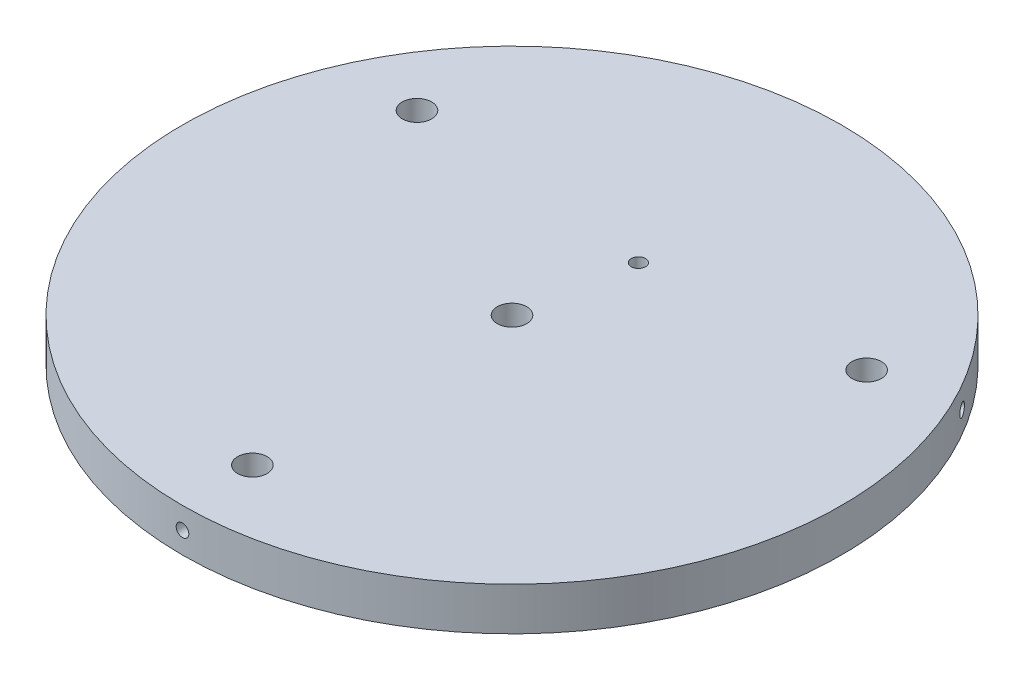
SolidWorks part; units mm, degrees
ref_plane "Front Plane" through (0, 0, 0) normal (0, 0, 1) x (1, 0, 0)
ref_plane "Top Plane" through (0, 0, 0) normal (0, 1, 0) x (1, 0, 0)
ref_plane "Right Plane" through (0, 0, 0) normal (1, 0, 0) x (0, 0, -1)
sketch "Sketch1" plane through (0, 0, 0) normal (0, 1, 0) x (1, 0, 0)
  line L0 (0, 0) -> (-63.2415, 36.5125) construction
  line L1 (0, 0) -> (0, -73.025) construction
  line L2 (0, 0) -> (63.2415, 36.5125) construction
  line L3 (0, 0) -> (7.2777, 23.8043) construction
  circle A0 centre (0, 0) radius 73.025
  circle A1 centre (-49.8233, 28.7655) radius 3.2639
  circle A2 centre (49.8233, 28.7655) radius 3.2639
  circle A3 centre (0, -57.531) radius 3.2639
  circle A4 centre (0, 0) radius 3.2639
  circle A5 centre (7.2777, 23.8043) radius 1.5875 construction
  point P15 (0, 0)
  dimension "D1" = 146.05
  dimension "D4" = 6.5278
  dimension "D7" = 6.5278
  dimension "D8" = 3.175
  dimension "D2" = 120
  dimension "D3" = 120
  dimension "D5" = 57.531
  dimension "D9" = 24.892
  dimension "D10" = 163
  dimension "D6" = 3
extrude "Boss-Extrude1" add sketch "Sketch1" along normal blind 9.525
ref_plane "Plane1" through (0, 0, 73.025) normal (0, 0, 1) x (1, 0, 0)
sketch "Sketch3" plane through (0, 0, 0) normal (0, 0, 1) x (1, 0, 0)
  line L0 (0, 0) -> (0, 9.525) construction
  line L1 (73.025, 9.525) -> (-73.025, 9.525) construction
sketch "Sketch4" plane through (0, 0, 73.025) normal (0, 0, 1) x (1, 0, 0)
  line L0 (0, 0) -> (0, 9.525) construction
  circle A0 centre (0, 4.7625) radius 1.397
  dimension "D1" = 2.794
extrude "Cut-Extrude1" cut sketch "Sketch4" against normal blind 6.35
pattern_circular "CirPattern1" count 3 over 360 about axis through (0, 0, 0) along (0, 1, 0) of "Cut-Extrude1"
sketch "Sketch5" plane through (0, 9.525, 0) normal (0, 1, 0) x (1, 0, 0)
  circle A0 centre (3.9182, 24.0893) radius 1.5875
  point P0 (3.9182, 24.0893)
  dimension "D1" = 3.175
extrude "Cut-Extrude2" cut sketch "Sketch5" against normal through all both
